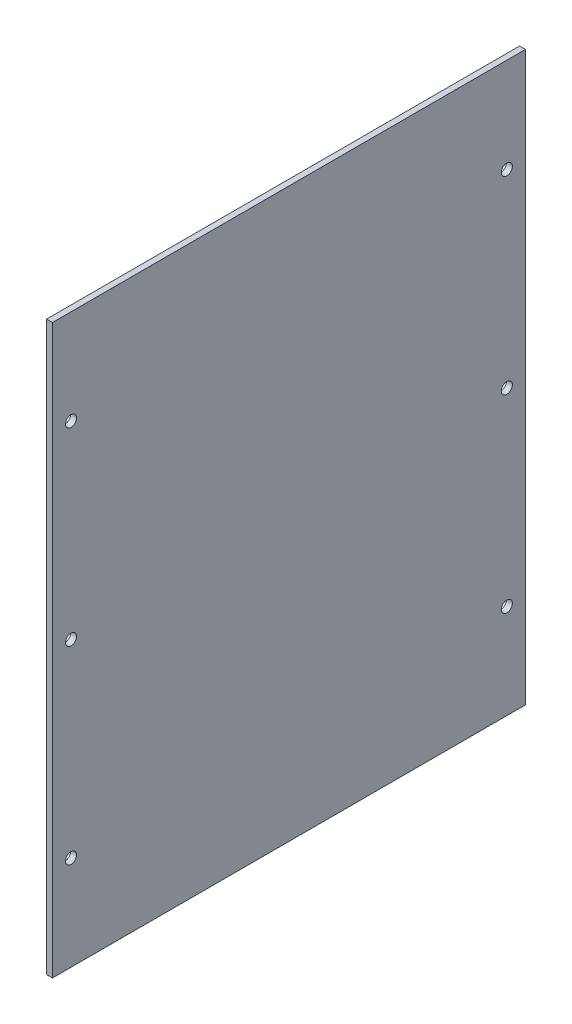
SolidWorks part; units mm, degrees
material "6061-T6 (SS)"
ref_plane "Front Plane" through (0, 0, 0) normal (0, 0, 1) x (1, 0, 0)
ref_plane "Top Plane" through (0, 0, 0) normal (0, 1, 0) x (1, 0, 0)
ref_plane "Right Plane" through (0, 0, 0) normal (1, 0, 0) x (0, 0, -1)
sketch "Sketch1" plane through (0, 0, 0) normal (0, 1, 0) x (1, 0, 0)
  line L1 (-1.5875, -127) -> (1.5875, -127)
  line L2 (-1.5875, -127) -> (-1.5875, 127)
  line L3 (-1.5875, 127) -> (1.5875, 127)
  line L4 (1.5875, -127) -> (1.5875, 127)
  line L5 (-1.5875, -127) -> (1.5875, 127) construction
  line L6 (-1.5875, 127) -> (1.5875, -127) construction
  point P0 (0, 0)
  dimension "D1" = 3.175
  dimension "D2" = 254
extrude "Boss-Extrude1" add sketch "Sketch1" along normal mid plane 304.8
sketch "Sketch2" plane through (1.5875, 0, 0) normal (1, 0, 0) x (0, 0, -1)
  line L0 (-278.2212, 0) -> (278.2212, 0) construction
  line L1 (0, -217.349) -> (0, 217.349) construction
  line L2 (127, 152.4) -> (127, -152.4) construction
  circle A0 centre (117, 0) radius 2.9718
  circle A1 centre (117, 101.6) radius 2.9718
  circle A2 centre (117, -101.6) radius 2.9718
  circle A3 centre (-117, 0) radius 2.9718
  circle A4 centre (-117, -101.6) radius 2.9718
  circle A5 centre (-117, 101.6) radius 2.9718
  point P4 (0, 0)
  point P8 (0, 0)
  dimension "D1" = 5.9436
  dimension "D2" = 10
  dimension "D3" = 2
extrude "Cut-Extrude1" cut sketch "Sketch2" against normal blind 3.175
